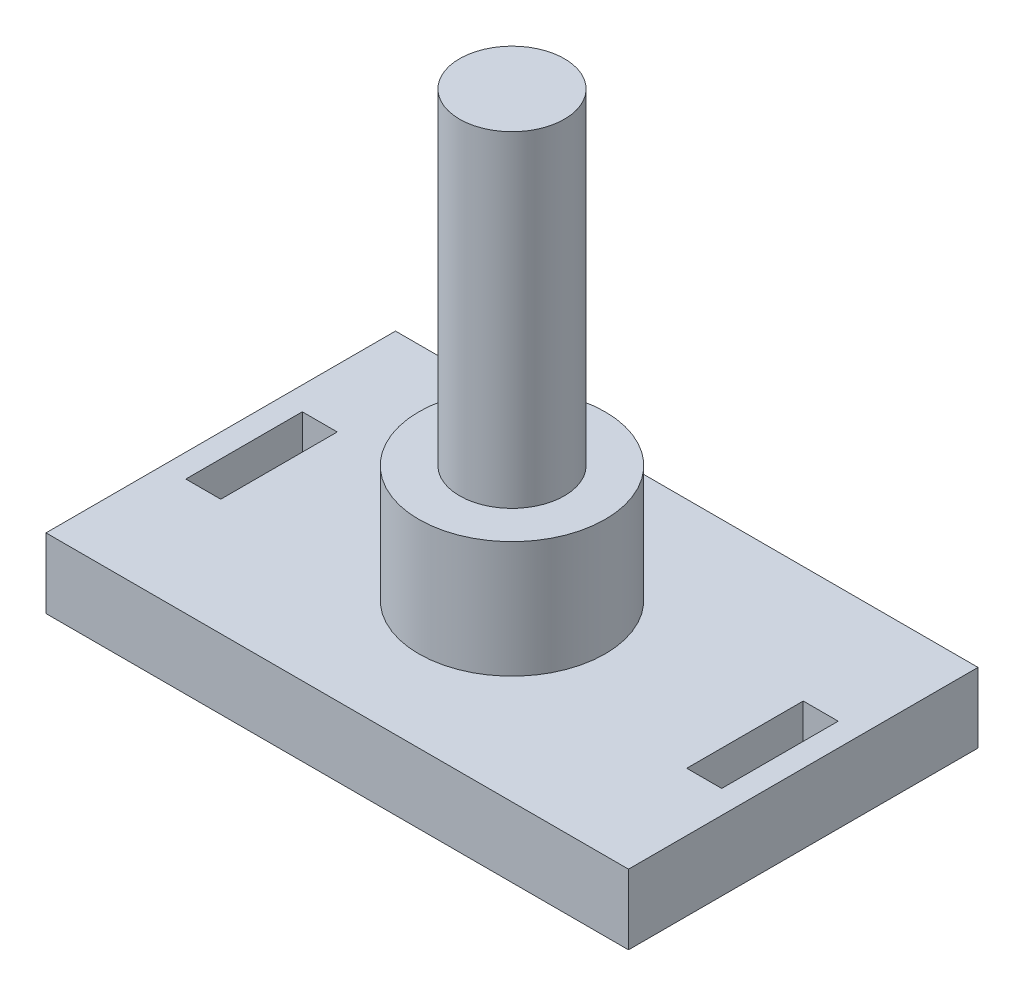
SolidWorks part; units mm, degrees
ref_plane "Front Plane" through (0, 0, 0) normal (0, 0, 1) x (1, 0, 0)
ref_plane "Top Plane" through (0, 0, 0) normal (0, 1, 0) x (1, 0, 0)
ref_plane "Right Plane" through (0, 0, 0) normal (1, 0, 0) x (0, 0, -1)
sketch "Sketch1" plane through (0, 0, 0) normal (0, 1, 0) x (1, 0, 0)
  circle A0 centre (0, 0) radius 2.25
  dimension "D1" = 4.5
extrude "Boss-Extrude1" add sketch "Sketch1" along normal blind 14 contours A0
sketch "Sketch2" plane through (0, 0, 0) normal (0, -1, 0) x (1, 0, 0)
  circle A0 centre (0, 0) radius 4
  dimension "D1" = 8
extrude "Boss-Extrude2" add sketch "Sketch2" along normal blind 5
sketch "Sketch3" plane through (0, -5, 0) normal (0, -1, 0) x (1, 0, 0)
  line L1 (-12.5, -7.5) -> (12.5, -7.5)
  line L2 (-12.5, -7.5) -> (-12.5, 7.5)
  line L3 (-12.5, 7.5) -> (12.5, 7.5)
  line L4 (12.5, -7.5) -> (12.5, 7.5)
  point P4 (0, 7.5)
  dimension "D3" = 7.5
  dimension "D1" = 25
  dimension "D2" = 15
  dimension "D4" = 12.5
extrude "Boss-Extrude3" add sketch "Sketch3" along normal blind 3 contours L2 L3 L4 L1
sketch "Sketch4" plane through (0, -8, 0) normal (0, -1, 0) x (1, 0, 0)
  line L0 (10, 0) -> (-10, 0) construction
  line L1 (12.5, -7.5) -> (12.5, 7.5) construction
  line L2 (-10, 2.5) -> (-11.5, 2.5)
  line L3 (-10, 2.5) -> (-10, -2.5)
  line L4 (-10, -2.5) -> (-11.5, -2.5)
  line L5 (-11.5, 2.5) -> (-11.5, -2.5)
  line L6 (10, 2.5) -> (11.5, 2.5)
  line L7 (10, 2.5) -> (10, -2.5)
  line L8 (10, -2.5) -> (11.5, -2.5)
  line L9 (11.5, 2.5) -> (11.5, -2.5)
  line L10 (-12.5, -7.5) -> (12.5, -7.5) construction
  point P4 (0, 0)
  dimension "D1" = 20
  dimension "D2" = 5
  dimension "D3" = 2.5
  dimension "D4" = 5
  dimension "D5" = 2.5
  dimension "D6" = 1.5
  dimension "D7" = 1.5
extrude "Cut-Extrude1" cut sketch "Sketch4" against normal blind 3
